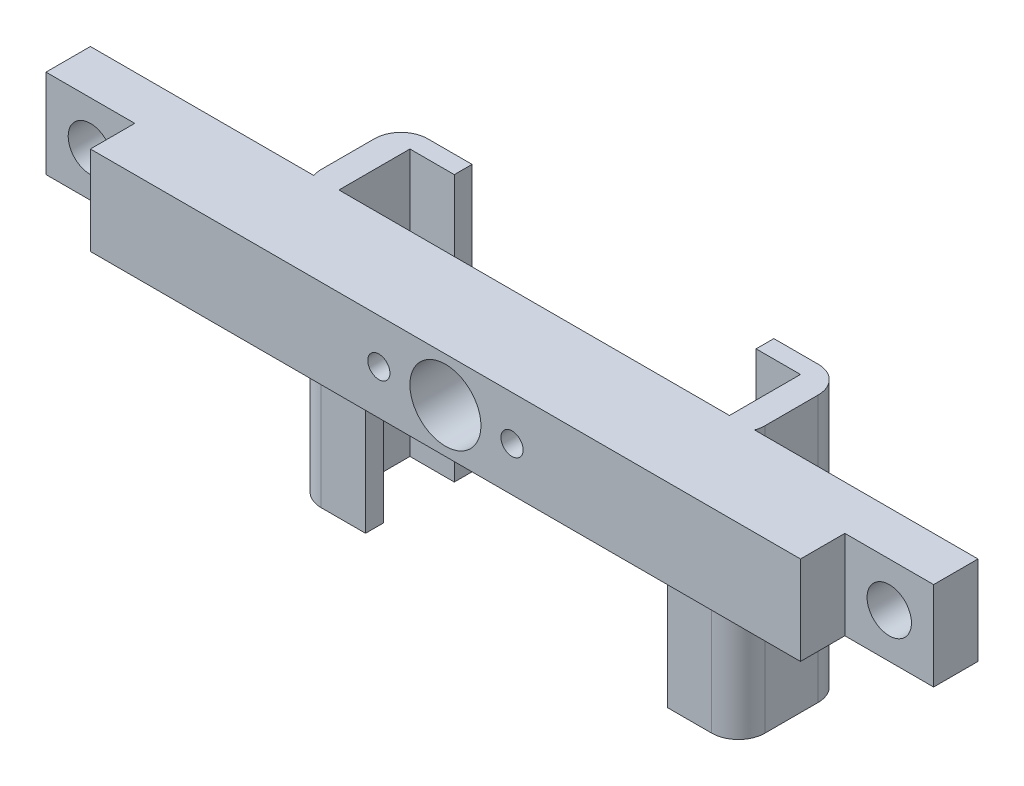
SolidWorks part; units mm, degrees
ref_plane "Front Plane" through (0, 0, 0) normal (0, 0, 1) x (1, 0, 0)
ref_plane "Top Plane" through (0, 0, 0) normal (0, 1, 0) x (1, 0, 0)
ref_plane "Right Plane" through (0, 0, 0) normal (1, 0, 0) x (0, 0, -1)
sketch "Sketch1" plane through (0, 0, 0) normal (0, 0, 1) x (1, 0, 0)
  line L1 (-50, 5) -> (50, 5)
  line L2 (-50, 5) -> (-50, -5)
  line L3 (-50, -5) -> (50, -5)
  line L4 (50, 5) -> (50, -5)
  line L5 (-50, 5) -> (50, -5) construction
  line L6 (-50, -5) -> (50, 5) construction
  point P0 (0, 0)
  dimension "D1" = 100
  dimension "D2" = 10
extrude "Boss-Extrude1" add sketch "Sketch1" along normal blind 10
sketch "Sketch2" plane through (0, 5, 0) normal (0, 1, 0) x (1, 0, 0)
  line L5 (-50, -10) -> (-40, -10)
  line L6 (-50, -10) -> (-50, -5)
  line L7 (-50, -5) -> (-40, -5)
  line L8 (-40, -10) -> (-40, -5)
  dimension "D1" = 10
  dimension "D2" = 5
sketch "Sketch6" plane through (0, 0, 0) normal (0, 0, -1) x (-1, 0, 0)
  line L0 (0, 5) -> (0, -5) construction
  line L1 (-25, 5) -> (-25, -5)
  line L3 (-25, 5) -> (-22, 5)
  line L4 (-50, 5) -> (-50, -5)
  line L5 (-50, -5) -> (50, -5)
  line L6 (-50, 5) -> (-50, -5)
  line L7 (50, 5) -> (-50, 5)
  line L9 (-50, -5) -> (50, -5)
  line L11 (50, 5) -> (-50, 5)
  line L12 (-22, 5) -> (-22, -5)
  line L13 (-22, -5) -> (-25, -5)
  line L17 (50, -5) -> (50, 5)
  line L18 (50, -5) -> (50, 5)
  line M11 (-50, -5) -> (50, -5)
  line M13 (50, 5) -> (-50, 5)
  dimension "D2" = 25
  dimension "D3" = 3
  dimension "D1" = 0
extrude "Boss-Extrude2" add sketch "Sketch6" along normal blind 10 contours L12 L1 M13 M11
sketch "Sketch8" plane through (22, 0, 0) normal (-1, 0, 0) x (0, 0, 1)
  line L0 (-10, -5) -> (0, -5) construction
  line L1 (-10, 5) -> (-8, 5)
  line L2 (-10, 5) -> (-10, -5)
  line L3 (-10, -5) -> (-8, -5)
  line L4 (-8, 5) -> (-8, -5)
  dimension "D1" = 2
extrude "Boss-Extrude3" add sketch "Sketch8" along normal blind 5
sketch "Sketch9" plane through (0, -5, 0) normal (0, -1, 0) x (1, 0, 0)
  line L0 (17, -10) -> (17, 0) construction
  line L1 (-50, 0) -> (22, 0) construction
  line L2 (17, 0) -> (22, 0)
  line L4 (17, 0) -> (17, 2)
  line L5 (17, 2) -> (25, 2)
  line L6 (25, 0) -> (25, 2)
  line L7 (22, 0) -> (22, -8)
  line L8 (22, -8) -> (17, -8)
  line L9 (17, -8) -> (17, -10)
  line L10 (17, -10) -> (25, -10)
  line L11 (25, -10) -> (25, 0)
  line L12 (25, 0) -> (25, 2)
  line L13 (-50, 10) -> (-50, 0) construction
  line L14 (-50, 10) -> (50, 10) construction
  line M16 (-50, 0) -> (22, 0)
  line M17 (22, 0) -> (22, -8)
  line M18 (22, -8) -> (17, -8)
  line M19 (17, -8) -> (17, -10)
  line M20 (17, -10) -> (25, -10)
  line M21 (25, -10) -> (25, 0)
  dimension "D1" = 8
  dimension "D2" = 2
  dimension "D3" = 2
extrude "Boss-Extrude4" add sketch "Sketch9" along normal blind 20 contours L6 L5 L4 M21 M16 M17 M18 M19 M20
mirror "Mirror3" about plane through (0, 0, 0) normal (1, 0, 0) of "Boss-Extrude4", "Boss-Extrude3", "Boss-Extrude2"
extrude "Cut-Extrude1" cut sketch "Sketch2" against normal blind 10
mirror "Mirror4" about plane through (0, 0, 0) normal (1, 0, 0) of "Cut-Extrude1"
sketch "Sketch10" plane through (0, 0, 5) normal (0, 0, 1) x (1, 0, 0)
  line L0 (50, -5) -> (50, 5) construction
  line L1 (40, -5) -> (50, -5) construction
  circle A0 centre (45, 0) radius 2.5
  dimension "D1" = 5
  dimension "D2" = 5
  dimension "D3" = 5
extrude "Cut-Extrude2" cut sketch "Sketch10" against normal up to next
mirror "Mirror5" about plane through (0, 0, 0) normal (1, 0, 0) of "Cut-Extrude2"
sketch "Sketch12" plane through (0, 0, 0) normal (0, 0, -1) x (-1, 0, 0)
  line L0 (0, 5) -> (0, -5) construction
  line L1 (-22, 5) -> (22, 5) construction
  line L2 (17, -5) -> (-17, -5) construction
sketch "Sketch13" plane through (0, 0, 0) normal (0, 0, -1) x (-1, 0, 0)
  line L0 (0, 0) -> (-7.5, 0) construction
  line L1 (0, 0) -> (7.5, 0) construction
  circle A0 centre (0, 0) radius 4
  circle A1 centre (-7.5, 0) radius 1.25
  circle A2 centre (7.5, 0) radius 1.25
  dimension "D1" = 8
  dimension "D4" = 2.5
  dimension "D5" = 2.5
  dimension "D2" = 7.5
  dimension "D3" = 7.5
extrude "Cut-Extrude3" cut sketch "Sketch13" against normal up to next
fillet "Fillet1" radius 3 2 edges at (25, -10, -10) (-25, -10, -10)
fillet "Fillet2" radius 3 2 edges at (-25, -15, 2) (25, -15, 2)
